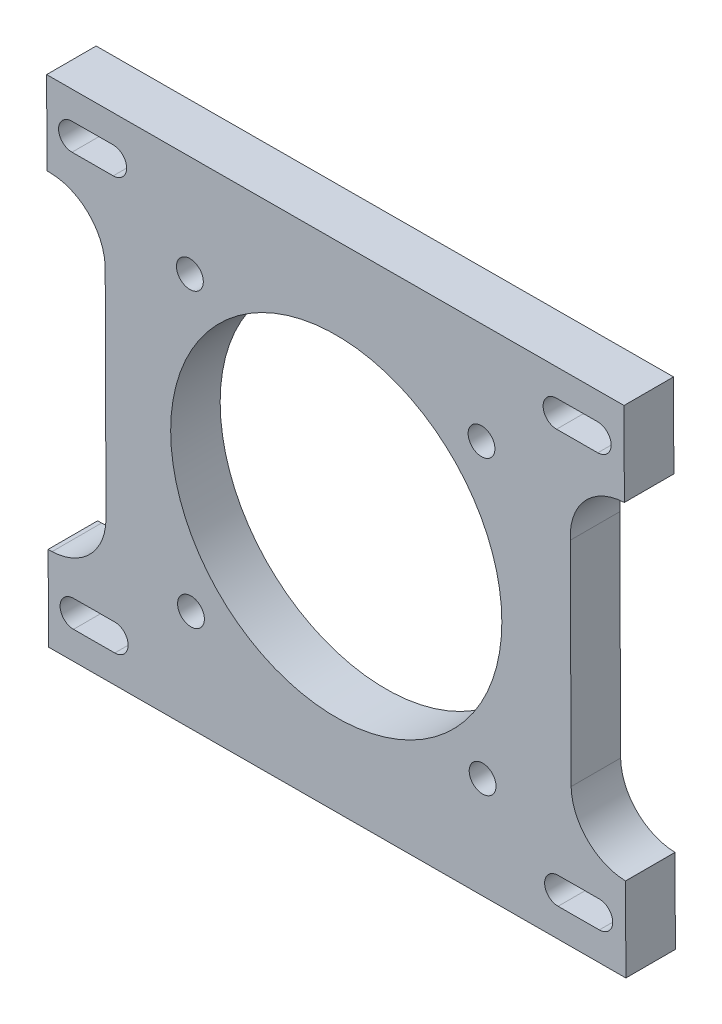
SolidWorks part; units mm, degrees
ref_plane "Front Plane" through (0, 0, 0) normal (0, 0, 1) x (1, 0, 0)
ref_plane "Top Plane" through (0, 0, 0) normal (0, 1, 0) x (1, 0, 0)
ref_plane "Right Plane" through (0, 0, 0) normal (1, 0, 0) x (0, 0, -1)
sketch "Sketch1" plane through (0, 0, 0) normal (0, 0, 1) x (1, 0, 0)
  circle B0 centre (2.0469, -5.7495) radius 40.1498
  circle B1 centre (-33.4387, 29.4747) radius 3.25
  circle B2 centre (-33.1773, -41.2352) radius 3.25
  circle B3 centre (37.5326, -40.9737) radius 3.25
  circle B4 centre (37.2711, 29.7362) radius 3.25
  line B5 (65.8107, -52.1104) -> (55.8109, -52.1473)
  arc B6 (65.8348, -58.6103) -> (65.8107, -52.1104) centre (65.8228, -55.3603) ccw
  line B7 (55.8349, -58.6473) -> (65.8348, -58.6103)
  arc B8 (55.8109, -52.1473) -> (55.8349, -58.6473) centre (55.8229, -55.3973) ccw
  line B9 (-61.6545, -59.2352) -> (-51.6546, -59.1982)
  arc B10 (-61.6786, -52.7352) -> (-61.6545, -59.2352) centre (-61.6665, -55.9852) ccw
  line B11 (-51.6787, -52.6983) -> (-61.6786, -52.7352)
  arc B12 (-51.6546, -59.1982) -> (-51.6787, -52.6983) centre (-51.6667, -55.9482) ccw
  line B13 (55.4651, 41.3516) -> (65.465, 41.3885)
  arc B14 (55.4411, 47.8515) -> (55.4651, 41.3516) centre (55.4531, 44.6015) ccw
  line B15 (65.441, 47.8885) -> (55.4411, 47.8515)
  arc B16 (65.465, 41.3885) -> (65.441, 47.8885) centre (65.453, 44.6385) ccw
  line B17 (-52.0485, 47.3006) -> (-62.0483, 47.2636)
  arc B18 (-62.0483, 47.2636) -> (-62.0243, 40.7637) centre (-62.0363, 44.0136) ccw
  line B19 (-62.0243, 40.7637) -> (-52.0244, 40.8006)
  arc B20 (-52.0244, 40.8006) -> (-52.0485, 47.3006) centre (-52.0364, 44.0506) ccw
  line B21 (-68.1741, 53.9909) -> (71.8242, 54.5086)
  line B22 (71.8242, 54.5086) -> (71.8994, 34.1713)
  line B23 (71.8994, 34.1713) -> (71.8995, 34.1695)
  arc B24 (71.8995, 34.1695) -> (58.7999, 19.7002) centre (72.3848, 20.5658) ccw
  line B25 (58.7999, 19.7002) -> (58.9888, -31.3925)
  line B26 (58.9888, -31.3925) -> (58.9908, -31.939)
  arc B27 (58.9908, -31.939) -> (72.1564, -45.1528) centre (72.5292, -31.6157) ccw
  line B28 (72.1564, -45.1528) -> (72.1928, -45.1526)
  line B29 (72.1928, -45.1526) -> (72.268, -65.4899)
  line B30 (72.268, -65.4899) -> (-67.7304, -66.0076)
  line B31 (-67.7304, -66.0076) -> (-67.8061, -45.5169)
  line B32 (-67.8061, -45.5169) -> (-66.8492, -45.5134)
  arc B33 (-66.8492, -45.5134) -> (-53.7817, -32.2026) centre (-67.3221, -31.9794) ccw
  line B34 (-53.7817, -32.2026) -> (-53.7837, -31.656)
  line B35 (-53.7837, -31.656) -> (-53.9727, 19.4366)
  arc B36 (-53.9727, 19.4366) -> (-67.2395, 33.8102) centre (-67.5636, 20.2017) ccw
  line B37 (-67.2395, 33.8102) -> (-68.0995, 33.8071)
  line B38 (-68.0995, 33.8071) -> (-68.1741, 53.9909)
sketch_block_instance "motorbevestiging V2019-1"
sketch_block "motorbevestiging V2019"
extrude "Boss-Extrude1" add sketch "Sketch1" along normal blind 12
